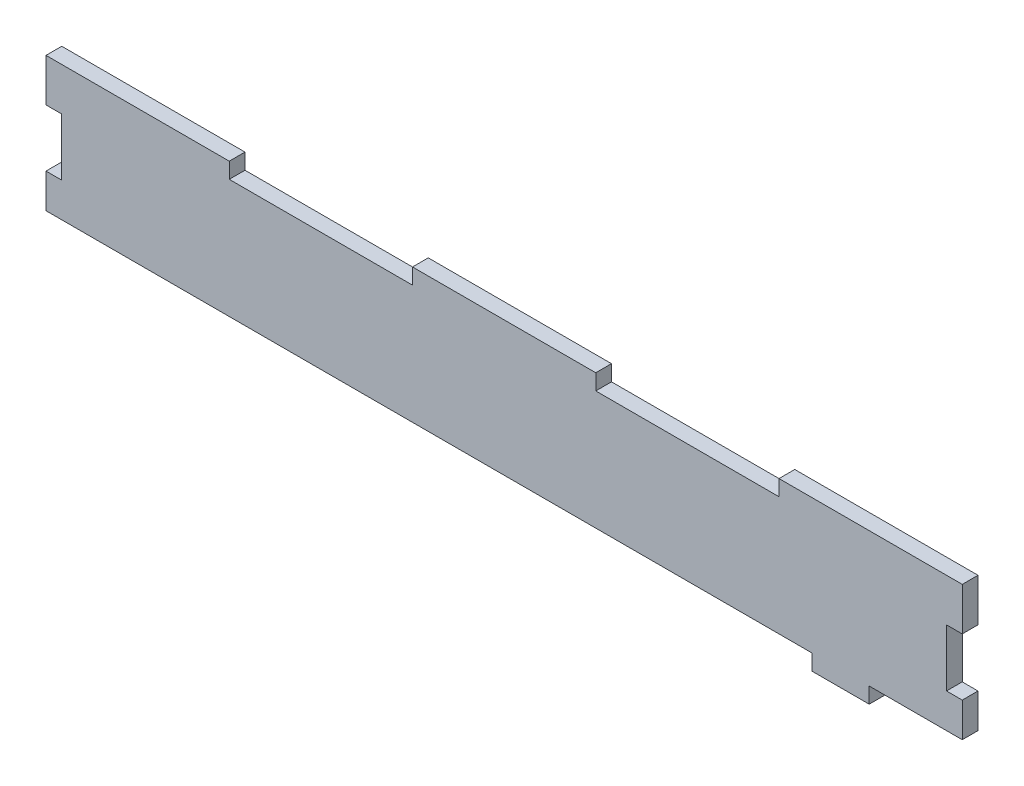
SolidWorks part; units mm, degrees
ref_plane "Alzado" through (0, 0, 0) normal (0, 0, 1) x (1, 0, 0)
ref_plane "Planta" through (0, 0, 0) normal (0, 1, 0) x (1, 0, 0)
ref_plane "Vista lateral" through (0, 0, 0) normal (1, 0, 0) x (0, 0, -1)
sketch "Croquis1" plane through (0, 0, 0) normal (0, 0, 1) x (1, 0, 0)
  line L0 (-63.7768, 3.3083) -> (-63.7768, 15.3083)
  line L1 (-63.7768, 15.3083) -> (-58.2768, 15.3083)
  line L2 (-58.2768, 15.3083) -> (-58.2768, 35.3083)
  line L3 (-58.2768, 35.3083) -> (-63.7768, 35.3083)
  line L4 (-63.7768, 35.3083) -> (-63.7768, 50.3083)
  line L5 (-63.7768, 50.3083) -> (0.2232, 50.3083)
  line L6 (0.2232, 50.3083) -> (0.2232, 44.8083)
  line L7 (0.2232, 44.8083) -> (64.2232, 44.8083)
  line L8 (64.2232, 44.8083) -> (64.2232, 50.3083)
  line L9 (64.2232, 50.3083) -> (128.2232, 50.3083)
  line L10 (128.2232, 50.3083) -> (128.2232, 44.8083)
  line L11 (128.2232, 44.8083) -> (192.2232, 44.8083)
  line L12 (192.2232, 44.8083) -> (192.2232, 50.3083)
  line L13 (192.2232, 50.3083) -> (256.2232, 50.3083)
  line L14 (256.2232, 50.3083) -> (256.2232, 35.3083)
  line L15 (256.2232, 35.3083) -> (250.7232, 35.3083)
  line L16 (250.7232, 35.3083) -> (250.7232, 15.3083)
  line L17 (250.7232, 15.3083) -> (256.2232, 15.3083)
  line L18 (256.2232, 15.3083) -> (256.2232, 3.3083)
  line L19 (256.2232, 3.3083) -> (223.7232, 3.3083)
  line L20 (223.7232, 3.3083) -> (223.7232, -2.1917)
  line L21 (223.7232, -2.1917) -> (203.7232, -2.1917)
  line L22 (203.7232, -2.1917) -> (203.7232, 3.3083)
  line L23 (203.7232, 3.3083) -> (-63.7768, 3.3083)
extrude "Saliente-Extruir1" add sketch "Croquis1" along normal blind 5.5
